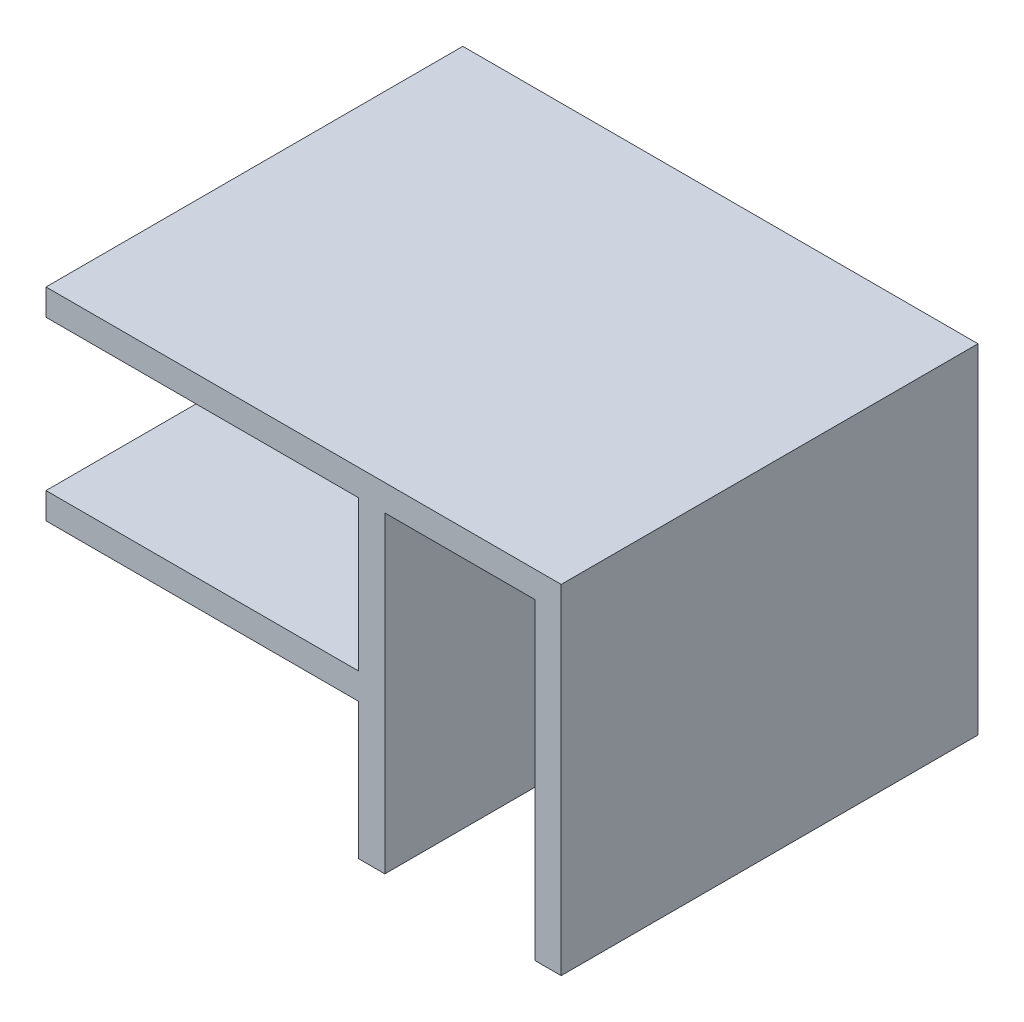
SolidWorks part; units mm, degrees
ref_plane "Front" through (0, 0, 0) normal (0, 0, 1) x (1, 0, 0)
ref_plane "Top" through (0, 0, 0) normal (0, 1, 0) x (1, 0, 0)
ref_plane "Right" through (0, 0, 0) normal (1, 0, 0) x (0, 0, -1)
sketch "Sketch2" plane through (0, 0, 0) normal (0, 0, 1) x (1, 0, 0)
  line L0 (0, 0) -> (0, 4.153)
  line L1 (0, 4.153) -> (-9.525, 4.153)
  line L2 (-9.525, 4.153) -> (-9.525, 4.953)
  line L3 (-9.525, 4.953) -> (0, 4.953)
  line L4 (0, 4.953) -> (0, 9.525)
  line L5 (0, 9.525) -> (-9.525, 9.525)
  line L6 (-9.525, 9.525) -> (-9.525, 10.325)
  line L7 (-9.525, 10.325) -> (6.172, 10.325)
  line L8 (6.172, 10.325) -> (6.172, 0)
  line L9 (6.172, 0) -> (5.372, 0)
  line L10 (5.372, 0) -> (5.372, 9.525)
  line L11 (5.372, 9.525) -> (0.8, 9.525)
  line L12 (0.8, 9.525) -> (0.8, 0)
  line L13 (0.8, 0) -> (0, 0)
  point P11 (0.0535, 0)
  point P16 (-9.525, 10.2213)
  dimension "D1" = 0.8
  dimension "D2" = 0.8
  dimension "D3" = 0.8
  dimension "D4" = 0.8
  dimension "D5" = 4.572
  dimension "D6" = 4.572
  dimension "D7" = 0.8
  dimension "D8" = 0.8
  dimension "D9" = 9.525
  dimension "D10" = 9.525
  dimension "D11" = 9.525
extrude "Boss-Extrude1" add sketch "Sketch2" along normal blind 12.7
